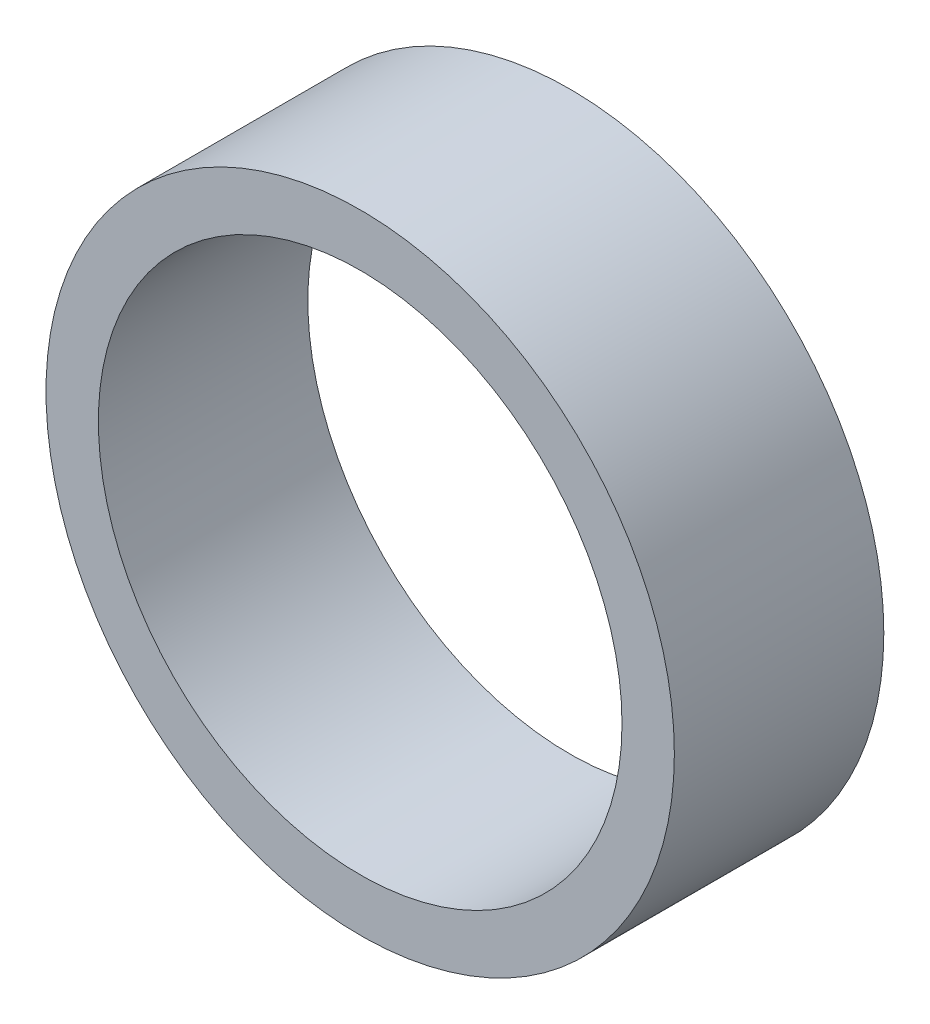
SolidWorks part; units mm, degrees
ref_plane "Front Plane" through (0, 0, 0) normal (1, 0, 0) x (0, 1, 0)
ref_plane "Top Plane" through (0, 0, 0) normal (0, 0, 1) x (0, 1, 0)
ref_plane "Right Plane" through (0, 0, 0) normal (0, 1, 0) x (-1, 0, 0)
sketch "Sketch1" plane through (0, 0, 0) normal (0, 0, 1) x (0, 1, 0)
  circle A0 centre (0, 0) radius 7.5
  circle A1 centre (0, 0) radius 6.25
  dimension "D1" = 15
  dimension "D2" = 12.5
extrude "Boss-Extrude1" add sketch "Sketch1" along normal blind 5
